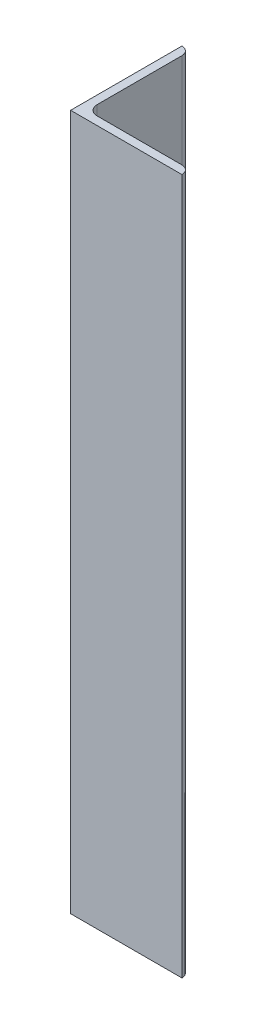
SolidWorks part; units mm, degrees
ref_plane "Front Plane" through (0, 0, 0) normal (0, 0, 1) x (1, 0, 0)
ref_plane "Top Plane" through (0, 0, 0) normal (0, 1, 0) x (1, 0, 0)
ref_plane "Right Plane" through (0, 0, 0) normal (1, 0, 0) x (0, 0, -1)
sketch3d "3DSketch1"
  line L0 (0, 0, 0) -> (0, 250, 0)
  dimension "D1" = 250
other "Iron V40X40X3(1)"
ref_plane "Plane1" through (0, 0, 0) normal (0, 1, 0) x (1, 0, 0)
sketch "Sketch11" plane through (0, 0, 0) normal (0, 1, 0) x (1, 0, 0)
  line L0 (0, 0) -> (0, 40)
  line L1 (0, 20) -> (3, 20) construction
  line L2 (3, 37) -> (3, 6.5)
  line L3 (6.5, 3) -> (37, 3)
  line L4 (20, 3) -> (20, 0) construction
  line L5 (40, 0) -> (0, 0)
  arc A0 (40, 0) -> (37, 3) centre (37, 0) ccw
  arc A1 (0, 40) -> (3, 37) centre (0, 37) cw
  arc A2 (6.5, 3) -> (3, 6.5) centre (6.5, 6.5) cw
  point P10 (20, 0)
  point P14 (0, 20)
  point P15 (3, 20)
  point P16 (20, 3)
  point P17 (3, 40)
  point P18 (40, 3)
  point P21 (0, 0)
  dimension "D2" = 3
  dimension "D3" = 40
  dimension "Radius_1" = 3.5
  dimension "D1" = 3
